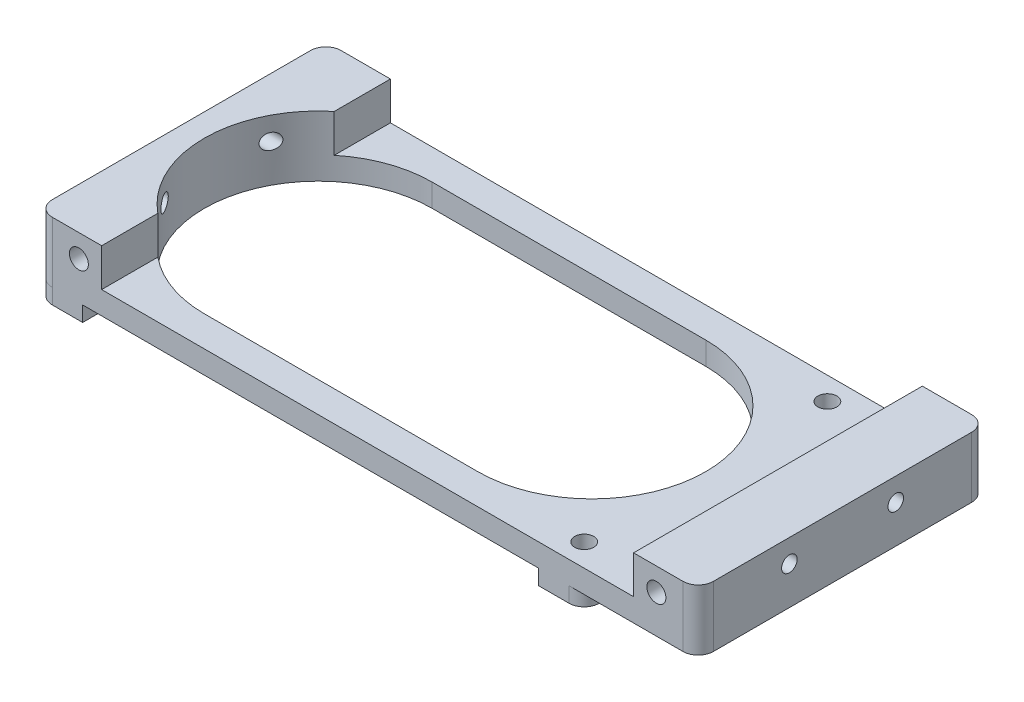
SolidWorks part; units mm, degrees
ref_plane "Front Plane" through (0, 0, 0) normal (0, 0, 1) x (1, 0, 0)
ref_plane "Top Plane" through (0, 0, 0) normal (0, 1, 0) x (1, 0, 0)
ref_plane "Right Plane" through (0, 0, 0) normal (1, 0, 0) x (0, 0, -1)
sketch "Sketch2" plane through (0, 0, 11.2) normal (0, 0, 1) x (1, 0, 0)
  line L1 (-84.0653, 85.9519) -> (-75.5653, 85.9519)
  line L2 (-84.0653, 85.9519) -> (-84.0653, 77.9519)
  line L3 (-84.0653, 77.9519) -> (2.9347, 77.9519)
  line L4 (2.9347, 85.9519) -> (2.9347, 77.9519)
  line L5 (-71.5653, 86.4519) -> (-82.0653, 86.4519) construction
  line L14 (-5.5653, 85.9519) -> (2.9347, 85.9519)
  line L16 (-75.5653, 85.9519) -> (-75.5653, 80.9519)
  line L17 (-75.5653, 80.9519) -> (-5.5653, 80.9519)
  line L18 (-5.5653, 85.9519) -> (-5.5653, 80.9519)
  dimension "D1" = 0.5
  dimension "D2" = 5.5
  dimension "D3" = 5.5
  dimension "D4" = 8
  dimension "D5" = 5
  dimension "D6" = 8.5
  dimension "D7" = 8.5
extrude "Boss-Extrude1" add sketch "Sketch2" along normal blind 38
fillet "Fillet3" radius 2 4 edges at (-84.0653, 81.9519, 49.2) (-84.0653, 81.9519, 11.2) (2.9347, 81.9519, 11.2) (2.9347, 81.9519, 49.2)
sketch "Sketch3" plane through (0, 80.9519, 0) normal (0, 1, 0) x (1, 0, 0)
  line L0 (-84.0653, -47.2) -> (-84.0653, -13.2) construction
  line L1 (-5.5653, -11.2) -> (-75.5653, -11.2) construction
  line L2 (-66.0653, -15.2) -> (-30.0653, -15.2)
  line L4 (-66.0653, -45.2) -> (-30.0653, -45.2)
  arc A0 (-30.0653, -45.2) -> (-30.0653, -15.2) centre (-30.0653, -30.2) ccw
  arc A1 (-66.0653, -15.2) -> (-66.0653, -45.2) centre (-66.0653, -30.2) ccw
  dimension "D1" = 30
  dimension "D2" = 18
  dimension "D3" = 36
  dimension "D4" = 19
extrude "Cut-Extrude1" cut sketch "Sketch3" against normal through all and the other way through all
hole_wizard "M3x0.5 Tapped Hole2" positions "Sketch6" profile "Sketch5" tap size "M3x0.5" standard "Ansi Metric"
sketch "Sketch6" plane through (0, 0, 11.2) normal (0, 0, -1) x (-1, 0, 0)
  line L1 (75.5653, 80.9519) -> (75.5653, 85.9519) construction
  line L2 (5.5653, 85.9519) -> (5.5653, 80.9519) construction
  line L3 (75.5653, 85.9519) -> (82.0653, 85.9519) construction
  line L4 (-0.9347, 85.9519) -> (5.5653, 85.9519) construction
  point P0 (78.5653, 82.9519)
  point P5 (2.5653, 82.9519)
  dimension "D1" = 3
  dimension "D2" = 3
  dimension "D3" = 3
  dimension "D4" = 3
sketch "Sketch5" plane through (-78.5653, 82.9519, 11.2) normal (1, 0, 0) x (0, 1, 0)
  line L0 (0, 0) -> (0, 8.2511)
  line L1 (0, 8.2511) -> (1.25, 7.5)
  line L2 (1.25, 7.5) -> (1.25, 0)
  line L5 (1.25, 0) -> (0, 0)
  line L10 (0, 8.2511) -> (-1.25, 7.5) construction
  line L11 (0, -6.35) -> (0, 107.95) construction
  dimension "Tap Drill Dia." = 2.5
  dimension "Tap Drill Depth" = 7.5
  dimension "Drill Angle" = 118
cosmetic thread "Hole Thread3" parameters "D1"=6, "D2"=3
cosmetic thread "Hole Thread4" parameters "D1"=6, "D2"=3
hole_wizard "M3x0.5 Tapped Hole3" positions "Sketch8" profile "Sketch7" tap size "M3x0.5" standard "Ansi Metric"
sketch "Sketch8" plane through (0, 0, 49.2) normal (0, 0, 1) x (1, 0, 0)
  line L0 (-5.5653, 85.9519) -> (-5.5653, 80.9519) construction
  line L2 (-75.5653, 85.9519) -> (-82.0653, 85.9519) construction
  line L3 (-75.5653, 80.9519) -> (-75.5653, 85.9519) construction
  line L4 (0.9347, 85.9519) -> (-5.5653, 85.9519) construction
  point P0 (-2.5653, 82.9519)
  point P1 (-78.5653, 82.9519)
  dimension "D1" = 3
  dimension "D2" = 3
  dimension "D3" = 3
  dimension "D4" = 3
sketch "Sketch7" plane through (-2.5653, 82.9519, 49.2) normal (1, 0, 0) x (0, -1, 0)
  line L0 (0, 0) -> (0, 8.2511)
  line L1 (0, 8.2511) -> (1.25, 7.5)
  line L2 (1.25, 7.5) -> (1.25, 0)
  line L5 (1.25, 0) -> (0, 0)
  line L10 (0, 8.2511) -> (-1.25, 7.5) construction
  line L11 (0, -6.35) -> (0, 107.95) construction
  dimension "Tap Drill Dia." = 2.5
  dimension "Tap Drill Depth" = 7.5
  dimension "Drill Angle" = 118
cosmetic thread "Hole Thread5" parameters "D1"=6, "D2"=3
cosmetic thread "Hole Thread6" parameters "D1"=6, "D2"=3
hole_wizard "M2.5x0.45 Tapped Hole1" positions "Sketch10" profile "Sketch9" tap size "M2.5x0.45" standard "Ansi Metric"
sketch "Sketch10" plane through (-84.0653, 0, 0) normal (-1, 0, 0) x (0, 0, 1)
  line L0 (30.2, 85.6523) -> (30.2, 71.6474) construction
  line L3 (47.2, 85.9519) -> (13.2, 85.9519) construction
  line L4 (49.2, 85.9519) -> (49.2, 77.9519) construction
  line L5 (11.2, 77.9519) -> (11.2, 85.9519) construction
  point P0 (37.2, 82.9519)
  point P1 (23.2, 82.9519)
  dimension "D1" = 12
  dimension "D2" = 3
  dimension "D3" = 3
  dimension "D4" = 12
sketch "Sketch9" plane through (-84.0653, 82.9519, 37.2) normal (0, 1, 0) x (0, 0, 1)
  line L0 (0, 0) -> (0, 6.9659)
  line L1 (0, 6.9659) -> (1.025, 6.35)
  line L2 (1.025, 6.35) -> (1.025, 0)
  line L5 (1.025, 0) -> (0, 0)
  line L10 (0, 6.9659) -> (-1.025, 6.35) construction
  line L11 (0, -6.35) -> (0, 107.95) construction
  dimension "Tap Drill Dia." = 2.05
  dimension "Tap Drill Depth" = 6.35
  dimension "Drill Angle" = 118
cosmetic thread "Hole Thread7" parameters "D1"=5, "D2"=2.5
cosmetic thread "Hole Thread8" parameters "D1"=5, "D2"=2.5
hole_wizard "M2.5x0.45 Tapped Hole2" positions "Sketch12" profile "Sketch11" tap size "M2.5x0.45" standard "Ansi Metric"
sketch "Sketch12" plane through (2.9347, 0, 0) normal (1, 0, 0) x (0, 0, -1)
  line L0 (-11.2, 85.9519) -> (-11.2, 77.9519) construction
  line L1 (-47.2, 85.9519) -> (-13.2, 85.9519) construction
  point P0 (-23.2, 82.9519)
  point P1 (-37.2, 82.9519)
  dimension "D1" = 12
  dimension "D2" = 3
  dimension "D3" = 3
  dimension "D4" = 14
sketch "Sketch11" plane through (2.9347, 82.9519, 23.2) normal (0, 1, 0) x (0, 0, -1)
  line L0 (0, 0) -> (0, 6.9659)
  line L1 (0, 6.9659) -> (1.025, 6.35)
  line L2 (1.025, 6.35) -> (1.025, 0)
  line L5 (1.025, 0) -> (0, 0)
  line L10 (0, 6.9659) -> (-1.025, 6.35) construction
  line L11 (0, -6.35) -> (0, 107.95) construction
  dimension "Tap Drill Dia." = 2.05
  dimension "Tap Drill Depth" = 6.35
  dimension "Drill Angle" = 118
cosmetic thread "Hole Thread9" parameters "D1"=5, "D2"=2.5
cosmetic thread "Hole Thread10" parameters "D1"=5, "D2"=2.5
sketch "Sketch13" plane through (0, 77.9519, 0) normal (0, -1, 0) x (1, 0, 0)
  line L1 (-84.0653, 11.2) -> (-78.0653, 11.2)
  line L2 (-84.0653, 11.2) -> (-84.0653, 17.2)
  line L3 (-84.0653, 17.2) -> (-78.0653, 17.2)
  line L4 (-78.0653, 11.2) -> (-78.0653, 17.2)
  line L5 (-84.0653, 47.2) -> (-84.0653, 13.2) construction
  line L6 (-84.0653, 49.2) -> (-78.0653, 49.2)
  line L7 (-84.0653, 49.2) -> (-84.0653, 43.2)
  line L8 (-84.0653, 43.2) -> (-78.0653, 43.2)
  line L10 (-78.0653, 49.2) -> (-78.0653, 43.2)
  line L11 (-82.0653, 49.2) -> (0.9347, 49.2) construction
  line L12 (-5.5653, 11.2) -> (-40.5653, 11.2) construction
  line L13 (-12.0653, 11.2) -> (-18.0653, 11.2)
  line L14 (-12.0653, 11.2) -> (-12.0653, 17.2)
  line L15 (-12.0653, 17.2) -> (-18.0653, 17.2)
  line L16 (-18.0653, 11.2) -> (-18.0653, 17.2)
  line L17 (-5.5653, 49.2) -> (-75.5653, 49.2) construction
  line L18 (-12.0653, 49.2) -> (-18.0653, 49.2)
  line L19 (-12.0653, 49.2) -> (-12.0653, 43.2)
  line L20 (-12.0653, 43.2) -> (-18.0653, 43.2)
  line L21 (-18.0653, 49.2) -> (-18.0653, 43.2)
  dimension "D1" = 6
  dimension "D2" = 6
  dimension "D3" = 6
  dimension "D4" = 6
  dimension "D5" = 6
  dimension "D6" = 6
  dimension "D7" = 60
  dimension "D8" = 60
  dimension "D9" = 6
  dimension "D10" = 6
extrude "Boss-Extrude3" add sketch "Sketch13" along normal blind 2
fillet "Fillet6" radius 2 8 edges at (-12.0653, 76.9519, 49.2) (-12.0653, 76.9519, 11.2) (-84.0653, 76.9519, 11.2) (-84.0653, 76.9519, 49.2) (-78.0653, 76.9519, 17.2) (-78.0653, 76.9519, 43.2) (-18.0653, 76.9519, 43.2) (-18.0653, 76.9519, 17.2)
hole_wizard "M3x0.5 Tapped Hole4" positions "Sketch15" profile "Sketch14" tap size "M3x0.5" standard "Ansi Metric"
sketch "Sketch15" plane through (0, 75.9519, 0) normal (0, -1, 0) x (1, 0, 0)
  line L0 (-12.0653, 17.2) -> (-16.0653, 17.2) construction
  line L1 (-18.0653, 15.2) -> (-18.0653, 11.2) construction
  line L2 (-18.0653, 49.2) -> (-18.0653, 45.2) construction
  line L4 (-16.0653, 43.2) -> (-12.0653, 43.2) construction
  line L5 (-84.0653, 43.2) -> (-80.0653, 43.2) construction
  line L7 (-78.0653, 45.2) -> (-78.0653, 49.2) construction
  line L8 (-80.0653, 17.2) -> (-84.0653, 17.2) construction
  line L9 (-84.0653, 17.2) -> (-84.0653, 13.2) construction
  point P0 (-15.0653, 46.2)
  point P1 (-15.0653, 14.2)
  point P3 (-81.0653, 14.2)
  point P5 (-81.0653, 46.2)
  dimension "D1" = 3
  dimension "D2" = 3
  dimension "D3" = 3
  dimension "D4" = 3
  dimension "D5" = 3
  dimension "D6" = 3
  dimension "D7" = 3
  dimension "D8" = 3
sketch "Sketch14" plane through (-15.0653, 75.9519, 46.2) normal (1, 0, 0) x (0, 0, -1)
  line L0 (0, 0) -> (0, 5.9511)
  line L1 (0, 5.9511) -> (1.25, 5.2)
  line L2 (1.25, 5.2) -> (1.25, 0)
  line L5 (1.25, 0) -> (0, 0)
  line L10 (0, 5.9511) -> (-1.25, 5.2) construction
  line L11 (0, -6.35) -> (0, 107.95) construction
  dimension "Tap Drill Dia." = 2.5
  dimension "Tap Drill Depth" = 5.2
  dimension "Drill Angle" = 118
cosmetic thread "Hole Thread11" parameters "D1"=5, "D2"=3
cosmetic thread "Hole Thread12" parameters "D1"=5, "D2"=3
cosmetic thread "Hole Thread13" parameters "D1"=5, "D2"=3
cosmetic thread "Hole Thread14" parameters "D1"=5, "D2"=3
